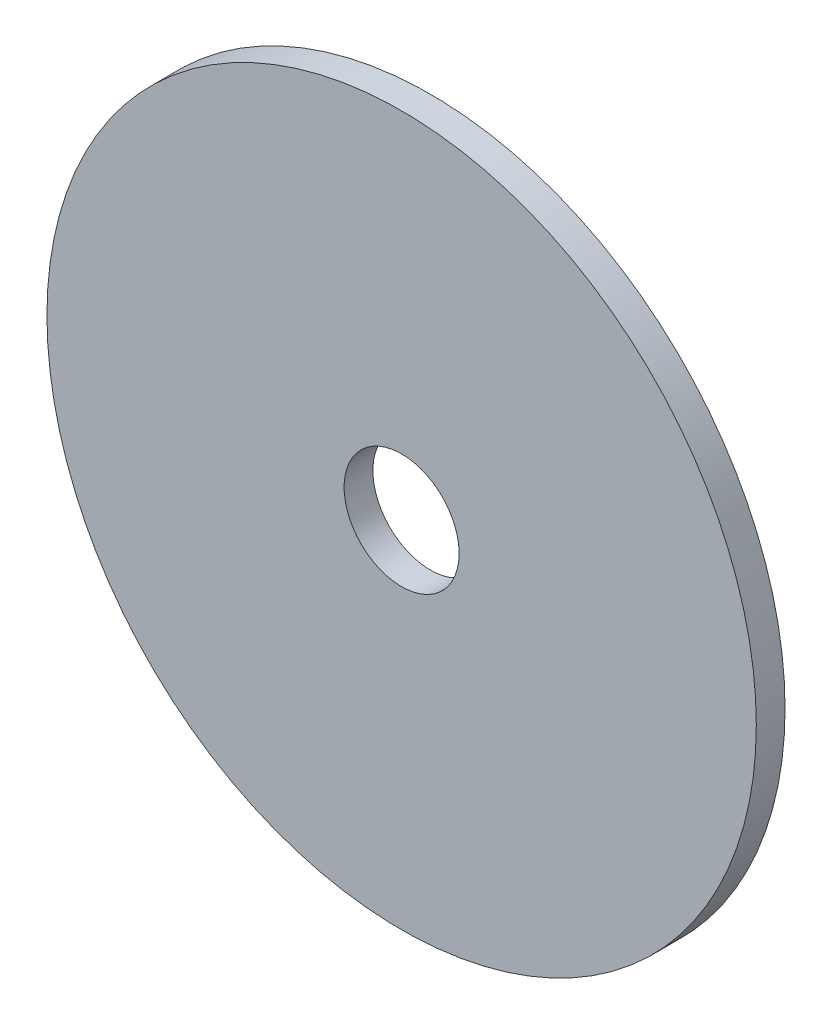
SolidWorks part; units mm, degrees
material "Acrylic (Medium-high impact)"
ref_plane "Front Plane" through (0, 0, 0) normal (0, 0, 1) x (1, 0, 0)
ref_plane "Top Plane" through (0, 0, 0) normal (0, 1, 0) x (1, 0, 0)
ref_plane "Right Plane" through (0, 0, 0) normal (1, 0, 0) x (0, 0, -1)
sketch "Model" plane through (0, 0, 0) normal (0, 0, 1) x (1, 0, 0)
  circle A0 centre (0, 0) radius 6
  circle A2 centre (0, 0) radius 37
  dimension "D1" = 12
  dimension "D2" = 74
extrude "Boss-Extrude2" add sketch "Model" along normal blind 3
